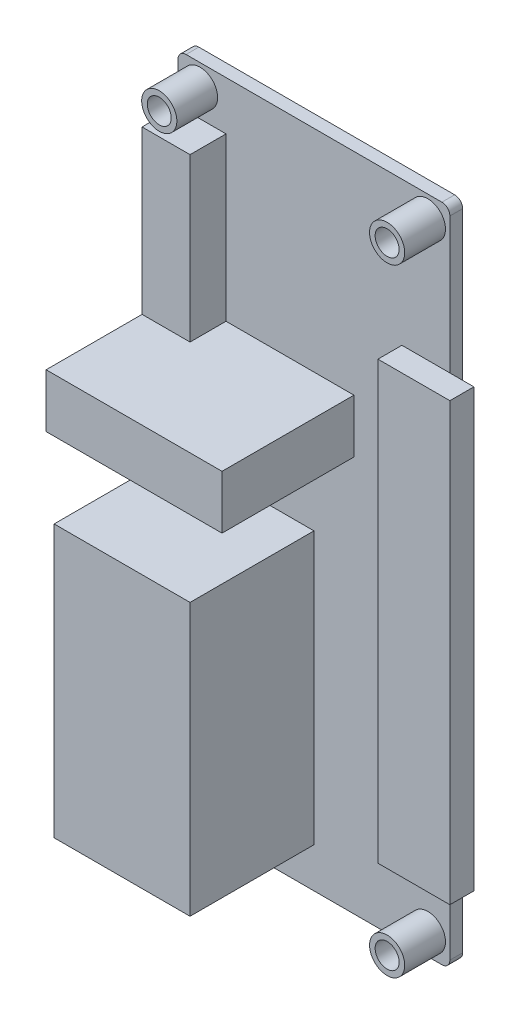
SolidWorks part; units mm, degrees
ref_plane "前视基准面" through (0, 0, 0) normal (0, 0, 1) x (1, 0, 0)
ref_plane "上视基准面" through (0, 0, 0) normal (0, 1, 0) x (1, 0, 0)
ref_plane "右视基准面" through (0, 0, 0) normal (1, 0, 0) x (0, 0, -1)
other "Configuration Table"
sketch "草图2" plane through (0, 0, 0) normal (0, 0, 1) x (1, 0, 0)
  line L1 (-16, -41.3) -> (16, -41.3)
  line L2 (-17, -40.3) -> (-17, 40.3)
  line L3 (-16, 41.3) -> (16, 41.3)
  line L4 (17, -40.3) -> (17, 40.3)
  line L5 (-17, -41.3) -> (17, 41.3) construction
  line L6 (-17, 41.3) -> (17, -41.3) construction
  line L7 (-14.25, -38.6) -> (14.25, -38.6) construction
  line L8 (-14.25, -38.6) -> (-14.25, 38.6) construction
  line L9 (-14.25, 38.6) -> (14.25, 38.6) construction
  line L10 (14.25, -38.6) -> (14.25, 38.6) construction
  line L11 (-14.25, -38.6) -> (14.25, 38.6) construction
  line L12 (-14.25, 38.6) -> (14.25, -38.6) construction
  arc A0 (16, -41.3) -> (17, -40.3) centre (16, -40.3) ccw
  arc A1 (-16, -41.3) -> (-17, -40.3) centre (-16, -40.3) cw
  arc A2 (-17, 40.3) -> (-16, 41.3) centre (-16, 40.3) cw
  arc A3 (16, 41.3) -> (17, 40.3) centre (16, 40.3) cw
  circle A4 centre (-14.25, 38.6) radius 1.5
  circle A5 centre (14.25, 38.6) radius 1.5
  circle A6 centre (-14.25, -38.6) radius 1.5
  circle A7 centre (14.25, -38.6) radius 1.5
  point P0 (0, 0)
  point P18 (0, 0)
  dimension "D3" = 1
  dimension "D6" = 3
  dimension "D1" = 34
  dimension "D2" = 82.6
  dimension "D4" = 28.5
  dimension "D5" = 77.2
extrude "凸台-拉伸1" add sketch "草图2" along normal blind 1.6
sketch "草图3" plane through (0, 0, 1.6) normal (0, 0, 1) x (1, 0, 0)
  line L0 (16, 41.3) -> (-16, 41.3) construction
  line L1 (11, 23.3) -> (20, 23.3)
  line L2 (11, 23.3) -> (11, -31.3)
  line L3 (11, -31.3) -> (20, -31.3)
  line L4 (20, 23.3) -> (20, -31.3)
  line L5 (17, -40.3) -> (17, 40.3) construction
  line L6 (-16, -41.3) -> (16, -41.3) construction
  dimension "D1" = 18
  dimension "D2" = 6
  dimension "D3" = 3
  dimension "D4" = 10
extrude "凸台-拉伸2" add sketch "草图3" along normal blind 3
sketch "草图4" plane through (0, 0, 1.6) normal (0, 0, 1) x (1, 0, 0)
  line L0 (-17, 40.3) -> (-17, -40.3) construction
  line L1 (-17, -2.3) -> (0, -2.3)
  line L2 (-17, -2.3) -> (-17, -36.3)
  line L3 (-17, -36.3) -> (0, -36.3)
  line L4 (0, -2.3) -> (0, -36.3)
  line L5 (-16, -41.3) -> (16, -41.3) construction
  dimension "D1" = 5
  dimension "D2" = 34
  dimension "D3" = 17
extrude "凸台-拉伸3" add sketch "草图4" along normal blind 15.5
sketch "草图5" plane through (0, 0, 1.6) normal (0, 0, 1) x (1, 0, 0)
  line L0 (-17, 40.3) -> (-17, -2.3) construction
  line L1 (-17, 8.2) -> (-10, 8.2)
  line L2 (-17, 8.2) -> (-17, -2.3)
  line L3 (-17, -2.3) -> (-10, -2.3)
  line L4 (-10, 8.2) -> (-10, -2.3)
  line L5 (0, -2.3) -> (-17, -2.3) construction
  line L6 (-16, -41.3) -> (16, -41.3) construction
  dimension "D1" = 49.5
  dimension "D2" = 7
extrude "凸台-拉伸4" add sketch "草图5" along normal blind 3.5
sketch "草图6" plane through (0, 0, 1.6) normal (0, 0, 1) x (1, 0, 0)
  circle A0 centre (-14.25, 38.6) radius 2.2
  circle A1 centre (14.25, 38.6) radius 2.2
  circle A2 centre (-14.25, -38.6) radius 2.2
  circle A3 centre (14.25, -38.6) radius 2.2
  circle A4 centre (14.25, -38.6) radius 1.5 construction
  circle A5 centre (-14.25, -38.6) radius 1.5 construction
  circle A6 centre (14.25, 38.6) radius 1.5 construction
  circle A7 centre (-14.25, 38.6) radius 1.5 construction
  circle A8 centre (14.25, -38.6) radius 1.5
  circle A9 centre (-14.25, -38.6) radius 1.5
  circle A10 centre (14.25, 38.6) radius 1.5
  circle A11 centre (-14.25, 38.6) radius 1.5
  dimension "D1" = 4.4
extrude "凸台-拉伸5" add sketch "草图6" along normal blind 5.1
sketch "草图7" plane through (0, 0, 1.6) normal (0, 0, 1) x (1, 0, 0)
  line L0 (-17, 40.3) -> (-17, 8.2) construction
  line L1 (-17, 14.9) -> (5, 14.9)
  line L2 (-17, 14.9) -> (-17, 8.2)
  line L3 (-17, 8.2) -> (5, 8.2)
  line L4 (5, 14.9) -> (5, 8.2)
  line L5 (-10, 8.2) -> (-17, 8.2) construction
  line L6 (-16, -41.3) -> (16, -41.3) construction
  point P6 (-17, 8.2)
  dimension "D1" = 56.2
  dimension "D2" = 22
extrude "凸台-拉伸6" add sketch "草图7" along normal blind 16.5
sketch "草图8" plane through (0, 0, 1.6) normal (0, 0, 1) x (1, 0, 0)
  line L0 (5, 14.9) -> (-17, 14.9) construction
  line L1 (-11, 14.9) -> (-17, 14.9)
  line L2 (-11, 14.9) -> (-11, 35.2)
  line L3 (-11, 35.2) -> (-17, 35.2)
  line L4 (-17, 14.9) -> (-17, 35.2)
  line L5 (-17, 40.3) -> (-17, 14.9) construction
  line L6 (-16, -41.3) -> (16, -41.3) construction
  dimension "D1" = 76.5
  dimension "D2" = 6
extrude "凸台-拉伸7" add sketch "草图8" along normal blind 4.5
